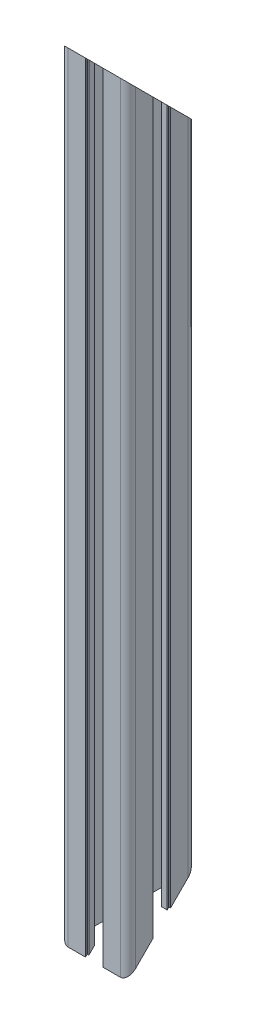
SolidWorks part; units mm, degrees
material "6061 Alloy"
ref_plane "Front Plane" through (0, 0, 0) normal (0, 0, 1) x (1, 0, 0)
ref_plane "Top Plane" through (0, 0, 0) normal (0, 1, 0) x (1, 0, 0)
ref_plane "Right Plane" through (0, 0, 0) normal (1, 0, 0) x (0, 0, -1)
other "Configuration Table"
sketch "Sketch3" plane through (0, 0, 0) normal (0, 1, 0) x (1, 0, 0)
  line L0 (10.25, -20.0897) -> (10.25, -10.25) construction
  line L1 (-15.5, 20) -> (15.5, 20)
  line L2 (-20, 15.5) -> (-20, -15.5)
  line L3 (-15.5, -20) -> (15.5, -20)
  line L4 (20, 15.5) -> (20, -15.5)
  line L5 (-20, 20) -> (20, -20) construction
  line L6 (-20, -20) -> (20, 20) construction
  line L7 (-7.7, 7.7) -> (7.7, 7.7)
  line L8 (-7.7, 7.7) -> (-7.7, -7.7)
  line L9 (-7.7, -7.7) -> (7.7, -7.7)
  line L10 (7.7, 7.7) -> (7.7, -7.7)
  line L11 (-7.7, 7.7) -> (7.7, -7.7) construction
  line L12 (-7.7, -7.7) -> (7.7, 7.7) construction
  line L13 (20, 20) -> (4.1, 20)
  line L14 (20, 20) -> (20, 4.1)
  line L15 (20, 4.1) -> (15.7, 4.1)
  line L16 (4.1, 20) -> (4.1, 15.7)
  line L17 (20, 20) -> (10.25, 20)
  line L18 (20, 20) -> (20, 10.25)
  line L19 (17, 10.25) -> (10.25, 10.25)
  line L20 (10.25, 17) -> (10.25, 10.25)
  line L21 (4.1, -20) -> (4.1, -4.1) construction
  line L22 (20, -4.1) -> (4.1, -4.1) construction
  line L23 (20, -10.25) -> (10.25, -10.25) construction
  line L32 (7.7, 5.9322) -> (12.0178, 10.25)
  line L33 (5.9322, 7.7) -> (10.25, 12.0178)
  line L34 (11.75, 17) -> (11.75, 12.75)
  line L35 (12.75, 11.75) -> (17, 11.75)
  line L36 (18, 12.75) -> (18, 15.5)
  line L37 (12.75, 18) -> (15.5, 18)
  line L38 (15.5, 4.3) -> (15.5, 5.6)
  line L39 (15.7, 5.8) -> (17, 5.8)
  line L40 (18, 6.8) -> (18, 9.25)
  line L41 (9.25, 18) -> (6.8, 18)
  line L42 (20, 4.1) -> (19, 4.1)
  line L43 (20, 4.1) -> (20, 5.1)
  line L44 (20, 5.1) -> (19.2, 5.1)
  line L45 (19, 4.1) -> (19, 4.9)
  line L46 (5.8, 17) -> (5.8, 15.7)
  line L47 (5.6, 15.5) -> (4.3, 15.5)
  line L48 (4.1, -20) -> (4.1, -15.7)
  line L49 (4.1, 20) -> (5.1, 20)
  line L50 (4.1, 20) -> (4.1, 19)
  line L51 (4.1, 19) -> (4.9, 19)
  line L52 (5.1, 20) -> (5.1, 19.2)
  line L53 (4.1, -19) -> (4.9, -19)
  line L54 (5.1, -20) -> (5.1, -19.2)
  line L55 (5.8, -15.7) -> (5.8, -17)
  line L56 (4.3, -15.5) -> (5.6, -15.5)
  line L57 (6.8, -18) -> (9.25, -18)
  line L58 (10.25, -17) -> (10.25, -10.25)
  line L59 (12.75, -18) -> (15.5, -18)
  line L60 (18, -12.75) -> (18, -15.5)
  line L61 (17, -11.75) -> (12.75, -11.75)
  line L62 (11.75, -12.75) -> (11.75, -17)
  line L63 (17, -10.25) -> (10.25, -10.25)
  line L64 (15.5, 20) -> (-15.5, 20)
  line L65 (20, 15.5) -> (20, -15.5)
  line L66 (15.5, -20) -> (-15.5, -20)
  line L67 (-20, 15.5) -> (-20, -15.5)
  line L68 (5.9322, -7.7) -> (10.25, -12.0178)
  line L69 (7.7, -5.9322) -> (12.0178, -10.25)
  line L70 (18, -9.25) -> (18, -6.8)
  line L71 (17, -5.8) -> (15.7, -5.8)
  line L72 (15.5, -5.6) -> (15.5, -4.3)
  line L73 (20, -4.1) -> (15.7, -4.1)
  line L74 (20, -5.1) -> (19.2, -5.1)
  line L75 (19, -4.1) -> (19, -4.9)
  line L76 (-20, -4.1) -> (-15.7, -4.1)
  line L77 (-19, -4.1) -> (-19, -4.9)
  line L78 (-20, -5.1) -> (-19.2, -5.1)
  line L79 (-15.7, -5.8) -> (-17, -5.8)
  line L80 (-15.5, -4.3) -> (-15.5, -5.6)
  line L81 (-18, -6.8) -> (-18, -9.25)
  line L82 (-17, -10.25) -> (-10.25, -10.25)
  line L83 (-18, -12.75) -> (-18, -15.5)
  line L84 (-12.75, -18) -> (-15.5, -18)
  line L85 (-11.75, -17) -> (-11.75, -12.75)
  line L86 (-12.75, -11.75) -> (-17, -11.75)
  line L87 (-10.25, -17) -> (-10.25, -10.25)
  line L88 (20, -15.5) -> (20, 15.5)
  line L89 (15.5, -20) -> (-15.5, -20)
  line L90 (-20, -15.5) -> (-20, 15.5)
  line L91 (15.5, 20) -> (-15.5, 20)
  line L92 (-7.7, -5.9322) -> (-12.0178, -10.25)
  line L93 (-5.9322, -7.7) -> (-10.25, -12.0178)
  line L94 (-9.25, -18) -> (-6.8, -18)
  line L95 (-5.8, -17) -> (-5.8, -15.7)
  line L96 (-5.6, -15.5) -> (-4.3, -15.5)
  line L97 (-4.1, -20) -> (-4.1, -15.7)
  line L98 (-5.1, -20) -> (-5.1, -19.2)
  line L99 (-4.1, -19) -> (-4.9, -19)
  line L100 (-4.1, 20) -> (-4.1, 15.7)
  line L101 (-4.1, 19) -> (-4.9, 19)
  line L102 (-5.1, 20) -> (-5.1, 19.2)
  line L103 (-5.8, 15.7) -> (-5.8, 17)
  line L104 (-4.3, 15.5) -> (-5.6, 15.5)
  line L105 (-6.8, 18) -> (-9.25, 18)
  line L106 (-10.25, 17) -> (-10.25, 10.25)
  line L107 (-12.75, 18) -> (-15.5, 18)
  line L108 (-18, 12.75) -> (-18, 15.5)
  line L109 (-17, 11.75) -> (-12.75, 11.75)
  line L110 (-11.75, 12.75) -> (-11.75, 17)
  line L111 (-17, 10.25) -> (-10.25, 10.25)
  line L112 (-15.5, -20) -> (15.5, -20)
  line L113 (-20, -15.5) -> (-20, 15.5)
  line L114 (-15.5, 20) -> (15.5, 20)
  line L115 (20, -15.5) -> (20, 15.5)
  line L116 (-5.9322, 7.7) -> (-10.25, 12.0178)
  line L117 (-7.7, 5.9322) -> (-12.0178, 10.25)
  line L118 (-18, 9.25) -> (-18, 6.8)
  line L119 (-17, 5.8) -> (-15.7, 5.8)
  line L120 (-15.5, 5.6) -> (-15.5, 4.3)
  line L121 (-20, 4.1) -> (-15.7, 4.1)
  line L122 (-20, 5.1) -> (-19.2, 5.1)
  line L123 (-19, 4.1) -> (-19, 4.9)
  line L124 (-20, 4.1) -> (-4.1, 4.1) [skipped]
  line L125 (-4.1, 20) -> (-4.1, 4.1) construction
  line L126 (-20, -4.1) -> (-4.1, -4.1) construction
  line L127 (-4.1, -20) -> (-4.1, -4.1) construction
  line L128 (-10.25, -19.9114) -> (-10.25, -10.25) [skipped]
  line L129 (-20.0897, -10.25) -> (-10.25, -10.25) [skipped]
  line L130 (-19.9114, 10.25) -> (-10.25, 10.25) [skipped]
  line L131 (-10.25, 20.0897) -> (-10.25, 10.25) [skipped]
  arc A0 (-15.5, 20) -> (-20, 15.5) centre (-15.5, 15.5) ccw
  arc A1 (15.5, -20) -> (20, -15.5) centre (15.5, -15.5) ccw
  arc A2 (-20, -15.5) -> (-15.5, -20) centre (-15.5, -15.5) ccw
  arc A3 (15.5, 20) -> (20, 15.5) centre (15.5, 15.5) cw
  arc A4 (15.5, 18) -> (18, 15.5) centre (15.5, 15.5) cw
  circle A5 centre (0, 0) radius 3.4
  arc A6 (17, 10.25) -> (18, 9.25) centre (17, 9.25) cw
  arc A7 (17, 5.8) -> (18, 6.8) centre (17, 6.8) ccw
  arc A8 (6.8, 18) -> (5.8, 17) centre (6.8, 17) ccw
  arc A9 (10.25, 17) -> (9.25, 18) centre (9.25, 17) ccw
  arc A10 (11.75, 17) -> (12.75, 18) centre (12.75, 17) cw
  arc A11 (17, 11.75) -> (18, 12.75) centre (17, 12.75) ccw
  arc A12 (12.75, 11.75) -> (11.75, 12.75) centre (12.75, 12.75) cw
  arc A13 (4.3, 15.5) -> (4.1, 15.7) centre (4.3, 15.7) cw
  arc A14 (15.7, 4.1) -> (15.5, 4.3) centre (15.7, 4.3) cw
  arc A15 (15.5, 5.6) -> (15.7, 5.8) centre (15.7, 5.6) cw
  arc A16 (19.2, 5.1) -> (19, 4.9) centre (19.2, 4.9) ccw
  arc A17 (4.9, 19) -> (5.1, 19.2) centre (4.9, 19.2) ccw
  arc A18 (5.8, 15.7) -> (5.6, 15.5) centre (5.6, 15.7) cw
  arc A19 (5.1, -19.2) -> (4.9, -19) centre (4.9, -19.2) ccw
  arc A20 (5.8, -17) -> (6.8, -18) centre (6.8, -17) ccw
  arc A21 (5.6, -15.5) -> (5.8, -15.7) centre (5.6, -15.7) cw
  arc A22 (4.1, -15.7) -> (4.3, -15.5) centre (4.3, -15.7) cw
  arc A23 (10.25, -17) -> (9.25, -18) centre (9.25, -17) cw
  arc A24 (11.75, -17) -> (12.75, -18) centre (12.75, -17) ccw
  arc A25 (18, -15.5) -> (15.5, -18) centre (15.5, -15.5) cw
  arc A26 (17, -11.75) -> (18, -12.75) centre (17, -12.75) cw
  arc A27 (11.75, -12.75) -> (12.75, -11.75) centre (12.75, -12.75) cw
  arc A28 (-15.5, 20) -> (-20, 15.5) centre (-15.5, 15.5) ccw
  arc A29 (20, 15.5) -> (15.5, 20) centre (15.5, 15.5) ccw
  arc A30 (20, -15.5) -> (15.5, -20) centre (15.5, -15.5) cw
  arc A31 (-20, -15.5) -> (-15.5, -20) centre (-15.5, -15.5) ccw
  arc A32 (17, -10.25) -> (18, -9.25) centre (17, -9.25) ccw
  arc A33 (18, -6.8) -> (17, -5.8) centre (17, -6.8) ccw
  arc A34 (15.7, -5.8) -> (15.5, -5.6) centre (15.7, -5.6) cw
  arc A35 (15.5, -4.3) -> (15.7, -4.1) centre (15.7, -4.3) cw
  arc A36 (19, -4.9) -> (19.2, -5.1) centre (19.2, -4.9) ccw
  arc A37 (-19.2, -5.1) -> (-19, -4.9) centre (-19.2, -4.9) ccw
  arc A38 (-17, -5.8) -> (-18, -6.8) centre (-17, -6.8) ccw
  arc A39 (-15.5, -5.6) -> (-15.7, -5.8) centre (-15.7, -5.6) cw
  arc A40 (-15.7, -4.1) -> (-15.5, -4.3) centre (-15.7, -4.3) cw
  arc A41 (-17, -10.25) -> (-18, -9.25) centre (-17, -9.25) cw
  arc A42 (-17, -11.75) -> (-18, -12.75) centre (-17, -12.75) ccw
  arc A43 (-15.5, -18) -> (-18, -15.5) centre (-15.5, -15.5) cw
  arc A44 (-11.75, -17) -> (-12.75, -18) centre (-12.75, -17) cw
  arc A45 (-12.75, -11.75) -> (-11.75, -12.75) centre (-12.75, -12.75) cw
  arc A46 (20, 15.5) -> (15.5, 20) centre (15.5, 15.5) ccw
  arc A47 (15.5, -20) -> (20, -15.5) centre (15.5, -15.5) ccw
  arc A48 (-15.5, -20) -> (-20, -15.5) centre (-15.5, -15.5) cw
  arc A49 (-15.5, 20) -> (-20, 15.5) centre (-15.5, 15.5) ccw
  arc A50 (-10.25, -17) -> (-9.25, -18) centre (-9.25, -17) ccw
  arc A51 (-6.8, -18) -> (-5.8, -17) centre (-6.8, -17) ccw
  arc A52 (-5.8, -15.7) -> (-5.6, -15.5) centre (-5.6, -15.7) cw
  arc A53 (-4.3, -15.5) -> (-4.1, -15.7) centre (-4.3, -15.7) cw
  arc A54 (-4.9, -19) -> (-5.1, -19.2) centre (-4.9, -19.2) ccw
  arc A55 (-5.1, 19.2) -> (-4.9, 19) centre (-4.9, 19.2) ccw
  arc A56 (-5.8, 17) -> (-6.8, 18) centre (-6.8, 17) ccw
  arc A57 (-5.6, 15.5) -> (-5.8, 15.7) centre (-5.6, 15.7) cw
  arc A58 (-4.1, 15.7) -> (-4.3, 15.5) centre (-4.3, 15.7) cw
  arc A59 (-10.25, 17) -> (-9.25, 18) centre (-9.25, 17) cw
  arc A60 (-11.75, 17) -> (-12.75, 18) centre (-12.75, 17) ccw
  arc A61 (-18, 15.5) -> (-15.5, 18) centre (-15.5, 15.5) cw
  arc A62 (-17, 11.75) -> (-18, 12.75) centre (-17, 12.75) cw
  arc A63 (-11.75, 12.75) -> (-12.75, 11.75) centre (-12.75, 12.75) cw
  arc A64 (15.5, -20) -> (20, -15.5) centre (15.5, -15.5) ccw
  arc A65 (-20, -15.5) -> (-15.5, -20) centre (-15.5, -15.5) ccw
  arc A66 (-20, 15.5) -> (-15.5, 20) centre (-15.5, 15.5) cw
  arc A67 (20, 15.5) -> (15.5, 20) centre (15.5, 15.5) ccw
  arc A68 (-17, 10.25) -> (-18, 9.25) centre (-17, 9.25) ccw
  arc A69 (-18, 6.8) -> (-17, 5.8) centre (-17, 6.8) ccw
  arc A70 (-15.7, 5.8) -> (-15.5, 5.6) centre (-15.7, 5.6) cw
  arc A71 (-15.5, 4.3) -> (-15.7, 4.1) centre (-15.7, 4.3) cw
  arc A72 (-19, 4.9) -> (-19.2, 5.1) centre (-19.2, 4.9) ccw
  point P0 (0, 0)
  point P6 (0, 0)
  point P84 (11.75, 18)
  point P87 (18, 11.75)
  point P90 (11.75, 11.75)
  point P101 (5.1, 19)
  dimension "D3" = 4.5
  dimension "D9" = 2
  dimension "D11" = 6.8
  dimension "D16" = 1
  dimension "D17" = 0.2
  dimension "D1" = 40
  dimension "D2" = 1
  dimension "D4" = 15.4
  dimension "D5" = 4
  dimension "D7" = 8.2
  dimension "D8" = 2.5
  dimension "D6" = 20.5
  dimension "D10" = 1.5
  dimension "D12" = 4.5
  dimension "D13" = 90
  dimension "D14" = 4.5
  dimension "D15" = 1
  dimension "D18" = 4
  dimension "D19" = 9.75
extrude "Boss-Extrude1" add sketch "Sketch3" along normal blind 500 contours L10 L7 L8 L9 A5 | L117 L8 L7 L116 L106 L111 | A72 L123 L121 A71 L120 A70 L119 A69 L118 A68 L111 L106 A59 L105 A56 L103 A57 L104 A58 L100 L101 A55 L102 L1 A0 L2 L122 L110 A63 L109 A62 L108 A61 L107 A60 | A18 L46 A8 L41 A9 L20 L19 A6 L40 A7 L39 A15 L38 A14 L15 L45 A16 L44 L14 L4 A3 L13 L52 A17 L51 L16 A13 L47 L35 A12 L34 A10 L37 A4 L36 A11 | L33 L7 L10 L32 L19 L20 | A36 L75 L73 A35 L72 A34 L71 A33 L70 A32 L63 L58 A23 L57 A20 L55 A21 L56 A22 L48 L53 A19 L54 L3 A1 L4 L74 L62 A27 L61 A26 L60 A25 L59 A24 | L69 L10 L9 L68 L58 L63 | L93 L9 L8 L92 L82 L87 | A54 L99 L97 A53 L96 A52 L95 A51 L94 A50 L87 L82 A41 L81 A38 L79 A39 L80 A40 L76 L77 A37 L78 L2 A2 L3 L98 L86 A45 L85 A44 L84 A43 L83 A42
sketch "Sketch4" plane through (0, 0, 0) normal (1, 0, 0) x (0, 0, -1)
  line L0 (-20, 0) -> (209.8097, 229.8097)
  line L1 (209.8097, 229.8097) -> (-20, 459.6194)
  line L2 (-20, 500) -> (-20, 0) construction
  line L3 (-20, 459.6194) -> (-20, 0)
  line L4 (-20, 459.6194) -> (-20, 500)
  line L5 (-20, 500) -> (20, 500)
  line L6 (20, 500) -> (20, 419.6194)
  line L7 (20, 500) -> (20, 0) construction
  line L8 (-20, 0) -> (20, 0)
  line L9 (20, 0) -> (20, 40)
  dimension "D1" = 325
extrude "Cut-Extrude1" cut sketch "Sketch4" against normal through all both and the other way through all contours L8 L9 L0 | L6 L5 L4 L1
